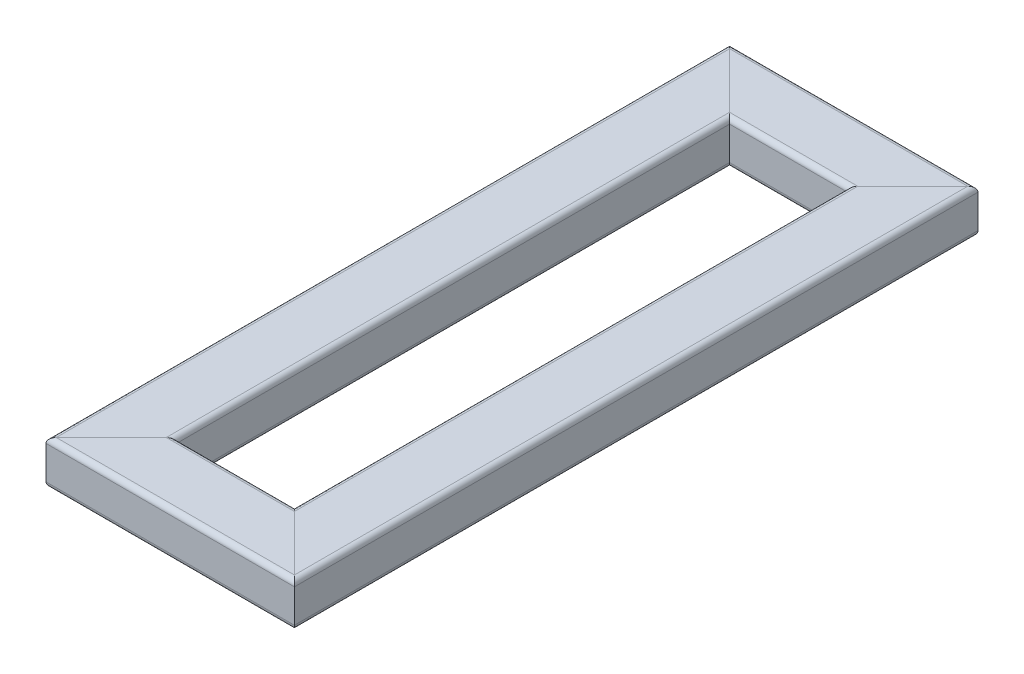
SolidWorks part; units mm, degrees
material "ASTM A36 Acero"
ref_plane "Alzado" through (0, 0, 0) normal (0, 0, 1) x (1, 0, 0)
ref_plane "Planta" through (0, 0, 0) normal (0, 1, 0) x (1, 0, 0)
ref_plane "Vista lateral" through (0, 0, 0) normal (1, 0, 0) x (0, 0, -1)
sketch "Croquis1" plane through (0, 0, 0) normal (0, 1, 0) x (1, 0, 0)
  line L1 (-145, 399) -> (145, 399)
  line L2 (-145, 399) -> (-145, -399)
  line L3 (-145, -399) -> (145, -399)
  line L4 (145, 399) -> (145, -399)
  line L5 (-145, 399) -> (145, -399) construction
  line L6 (-145, -399) -> (145, 399) construction
  point P0 (0, 0)
  dimension "D1" = 798
  dimension "D2" = 290
other "Tubo rectangular 3 X 2 X 0.25(1)"
ref_plane "Plano1" through (-106.9, 25.4, -399) normal (0, 0, 1) x (1, 0, 0)
sketch "Sketch1" plane through (-106.9, 25.4, -399) normal (0, 0, 1) x (1, 0, 0)
  line L0 (-32.1, -22.4) -> (32.1, -22.4)
  line L1 (-35.1, -19.4) -> (-35.1, 19.4)
  line L2 (32.1, 22.4) -> (-32.1, 22.4)
  line L3 (35.1, 19.4) -> (35.1, -19.4)
  line L4 (-32.1, -25.4) -> (32.1, -25.4)
  line L5 (-38.1, -19.4) -> (-38.1, 19.4)
  line L6 (32.1, 25.4) -> (-32.1, 25.4)
  line L7 (38.1, 19.4) -> (38.1, -19.4)
  line L8 (0, 0) -> (38.1, 0) construction
  line L9 (0, 0) -> (0, 25.4) construction
  arc A0 (38.1, 19.4) -> (32.1, 25.4) centre (32.1, 19.4) ccw
  arc A1 (32.1, -25.4) -> (38.1, -19.4) centre (32.1, -19.4) ccw
  arc A2 (-38.1, -19.4) -> (-32.1, -25.4) centre (-32.1, -19.4) ccw
  arc A3 (-32.1, 25.4) -> (-38.1, 19.4) centre (-32.1, 19.4) ccw
  arc A4 (-32.1, 22.4) -> (-35.1, 19.4) centre (-32.1, 19.4) ccw
  arc A5 (35.1, 19.4) -> (32.1, 22.4) centre (32.1, 19.4) ccw
  arc A6 (32.1, -22.4) -> (35.1, -19.4) centre (32.1, -19.4) ccw
  arc A7 (-35.1, -19.4) -> (-32.1, -22.4) centre (-32.1, -19.4) ccw
  point P3 (0, -25.4)
  point P4 (-38.1, 0)
  point P5 (0, 0)
  point P6 (38.1, -25.4)
  point P7 (-38.1, -25.4)
  point P8 (-38.1, 25.4)
  point P33 (0, 0)
  point P35 (38.1, 25.4)
  point P36 (38.1, 0)
  point P37 (0, 25.4)
  dimension "D1" = 6
  dimension "Thickness" = 3
  dimension "V_leg" = 50.8
  dimension "H_leg" = 76.2
